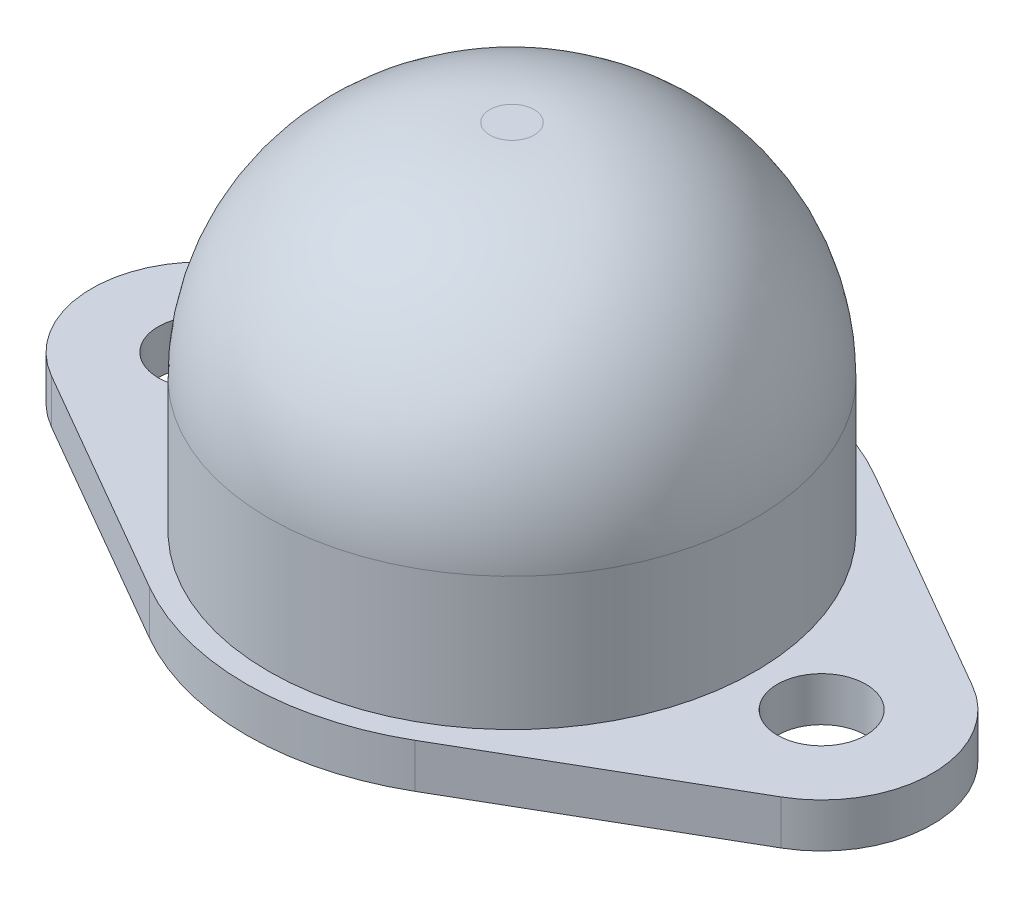
SolidWorks part; units mm, degrees
ref_plane "Front Plane" through (0, 0, 0) normal (0, 0, 1) x (1, 0, 0)
ref_plane "Top Plane" through (0, 0, 0) normal (0, 1, 0) x (1, 0, 0)
ref_plane "Right Plane" through (0, 0, 0) normal (1, 0, 0) x (0, 0, -1)
sketch "Sketch1" plane through (0, 0, 0) normal (0, 1, 0) x (1, 0, 0)
  line L0 (-20.1459, 0) -> (16.8477, 0) construction
  line L1 (-8.25, 2.1651) -> (-3, 5.1962)
  line L2 (3, 5.1962) -> (8.25, 2.1651)
  line L3 (8.25, 2.1651) -> (8.25, -2.1651)
  line L4 (8.25, -2.1651) -> (3, -5.1962)
  line L5 (3, -5.1962) -> (-3, -5.1962)
  line L6 (-3, -5.1962) -> (-8.25, -2.1651)
  circle A0 centre (0, 0) radius 6
  circle A1 centre (-7, 0) radius 2.5
  circle A2 centre (7, 0) radius 2.5
  circle A3 centre (-7, 0) radius 1
  circle A4 centre (7, 0) radius 1
  point P9 (-9.5, 0)
  point P10 (9.5, 0)
  dimension "D1" = 12
  dimension "D2" = 5
  dimension "D3" = 5
  dimension "D6" = 2
  dimension "D7" = 2
  dimension "D4" = 19
  dimension "D5" = 9.5
extrude "Boss-Extrude1" add sketch "Sketch1" along normal blind 1 contours A1 L0 A3 A0 | L0 A1 A0 A3 | L0 A0 A1 | A0 L0 A1 | A1 A0 L1 | A1 L6 A0 | L0 A1 A0 L5 A2 | A1 L0 A2 A0 | L5 A0 | A2 L2 A0 | A2 A0 L4 | L0 A2 A0 | A2 L0 A0 | L0 A4 A0 A2 L3 | A4 L0 L3 A2 A0 | L3 L0 A2 | L0 L3 A2
sketch "Sketch2" plane through (0, 1, 0) normal (0, 1, 0) x (1, 0, 0)
  circle A0 centre (0, 0) radius 5.5
  dimension "D1" = 11
extrude "Boss-Extrude2" add sketch "Sketch2" along normal blind 8
fillet "Fillet1" radius 5 1 edges at (0, 9, 5.5)
